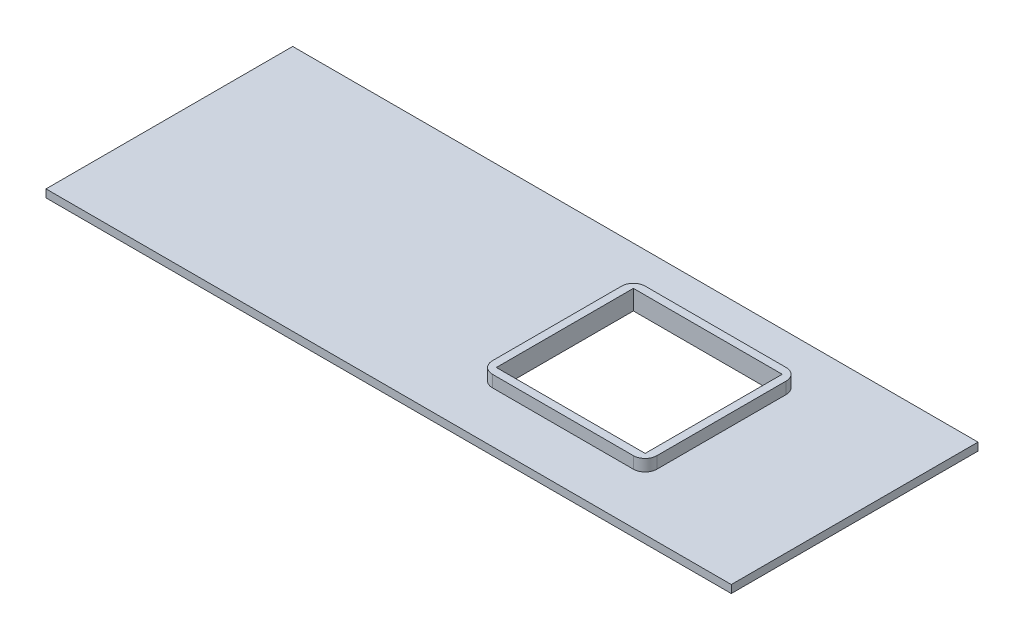
SolidWorks part; units mm, degrees
ref_plane "Front Plane" through (0, 0, 0) normal (0, 0, 1) x (1, 0, 0)
ref_plane "Top Plane" through (0, 0, 0) normal (0, 1, 0) x (1, 0, 0)
ref_plane "Right Plane" through (0, 0, 0) normal (1, 0, 0) x (0, 0, -1)
other "Configuration Table"
sketch "Sketch1" plane through (0, 0, 0) normal (0, 1, 0) x (1, 0, 0)
  line L1 (-37.3895, 27.1848) -> (0.6105, 27.1848)
  line L2 (-37.3895, 27.1848) -> (-37.3895, -7.8152)
  line L3 (-37.3895, -7.8152) -> (0.6105, -7.8152)
  line L4 (0.6105, 27.1848) -> (0.6105, -7.8152)
  line L5 (-39.3895, 29.1848) -> (2.6105, 29.1848)
  line L6 (-39.3895, 29.1848) -> (-39.3895, -9.8152)
  line L7 (-39.3895, -9.8152) -> (2.6105, -9.8152)
  line L8 (2.6105, 29.1848) -> (2.6105, -9.8152)
  dimension "D1" = 38
  dimension "D2" = 35
  dimension "D3" = 39
  dimension "D4" = 42
  dimension "D5" = 2
  dimension "D6" = 2
extrude "Boss-Extrude1" add sketch "Sketch1" along normal blind 3
fillet "Fillet2" radius 3 4 edges at (-39.3895, 1.5, -29.1848) (2.6105, 1.5, -29.1848) (2.6105, 1.5, 9.8152) (-39.3895, 1.5, 9.8152)
sketch "Sketch5" plane through (0, 0, 0) normal (0, -1, 0) x (1, 0, 0)
  line L0 (2.6105, 6.8152) -> (2.6105, -26.1848) construction
  line L1 (-137.3895, 22.8152) -> (37.6105, 22.8152)
  line L2 (-137.3895, 22.8152) -> (-137.3895, -40.1848)
  line L3 (-137.3895, -40.1848) -> (37.6105, -40.1848)
  line L4 (37.6105, 22.8152) -> (37.6105, -40.1848)
  line L5 (-36.3895, 9.8152) -> (-0.3895, 9.8152) construction
  line L9 (-37.3895, 7.8152) -> (0.6105, 7.8152)
  line L10 (-37.3895, 7.8152) -> (-37.3895, -27.1848)
  line L11 (-37.3895, -27.1848) -> (0.6105, -27.1848)
  line L12 (0.6105, 7.8152) -> (0.6105, -27.1848)
  dimension "D1" = 175
  dimension "D2" = 63
  dimension "D3" = 35
  dimension "D4" = 13
extrude "Boss-Extrude2" add sketch "Sketch5" along normal blind 2
